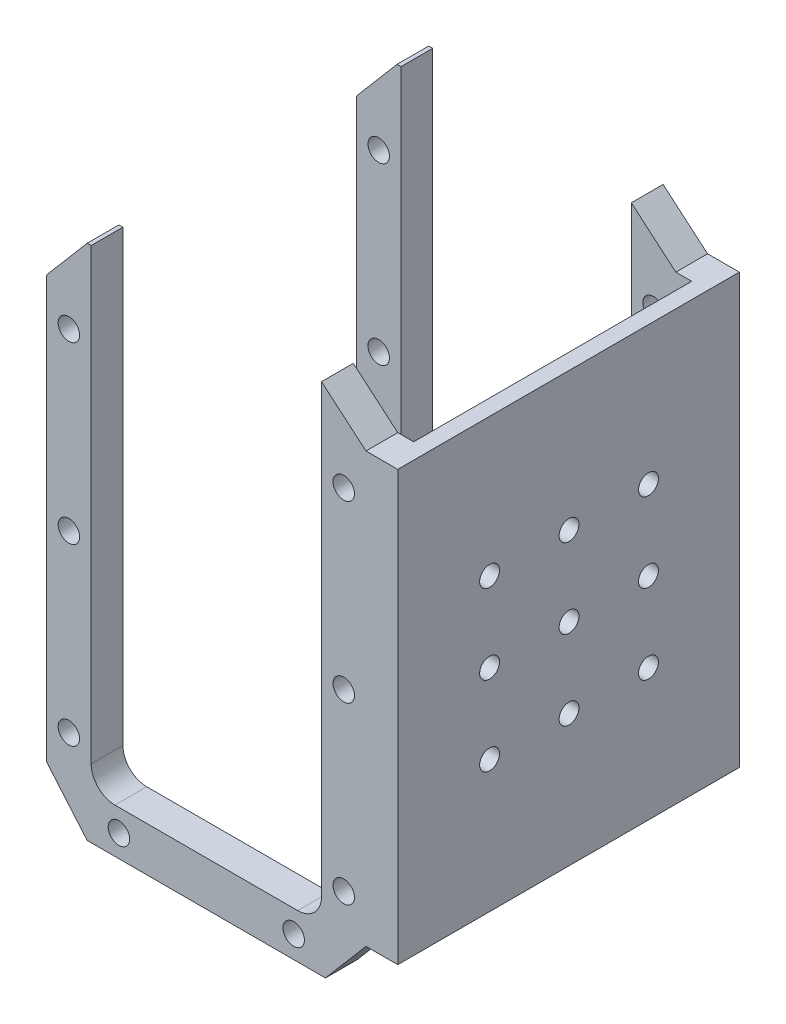
SolidWorks part; units mm, degrees
ref_plane "정면" through (0, 0, 0) normal (0, 0, 1) x (1, 0, 0)
ref_plane "윗면" through (0, 0, 0) normal (0, 1, 0) x (1, 0, 0)
ref_plane "우측면" through (0, 0, 0) normal (1, 0, 0) x (0, 0, -1)
sketch "스케치2" plane through (0, 0, 0) normal (0, 0, 1) x (1, 0, 0)
  line L0 (-19.9258, 26.8349) -> (-19.9258, -26.2651)
  line L1 (-19.9258, -26.2651) -> (-14.8258, -32.2651)
  line L2 (-14.8258, -32.2651) -> (15.1742, -32.2651)
  line L3 (15.1742, -32.2651) -> (20.2742, -26.2651)
  line L4 (20.2742, -26.2651) -> (20.2742, 27.7349)
  line L5 (20.2742, 27.7349) -> (14.6742, 32.4949)
  line L7 (14.6742, 29.8349) -> (14.6742, -23.6651)
  line L8 (11.6742, -26.6651) -> (-11.3258, -26.6651)
  line L9 (-14.3258, -23.6651) -> (-14.3258, 29.8349)
  line L10 (-14.3258, 32.8349) -> (-14.8258, 32.8349)
  line L11 (-14.8258, 32.8349) -> (-19.9258, 26.8349)
  line L12 (-14.3258, 29.8349) -> (-14.3258, 32.8349)
  line L13 (14.6742, 32.4949) -> (14.6742, 29.8349)
  circle A0 centre (17.4742, -21.6651) radius 1.35
  arc A2 (11.6742, -26.6651) -> (14.6742, -23.6651) centre (11.6742, -23.6651) ccw
  arc A3 (-14.3258, -23.6651) -> (-11.3258, -26.6651) centre (-11.3258, -23.6651) ccw
  circle A5 centre (-17.1258, 22.3349) radius 1.35
  circle A6 centre (-17.1258, 0.3349) radius 1.35
  circle A7 centre (-17.1258, -21.6651) radius 1.35
  circle A8 centre (-10.8258, -29.4651) radius 1.35
  circle A9 centre (11.1742, -29.4651) radius 1.35
  circle A10 centre (17.4742, 0.3349) radius 1.35
  circle A11 centre (17.4742, 22.3349) radius 1.35
  dimension "D1" = 2.7
  dimension "D2" = 3
  dimension "D3" = 11.1742
  dimension "D4" = 14.6742
  dimension "D5" = 15.1742
  dimension "D6" = 17.4742
  dimension "D7" = 20.2742
  dimension "D8" = 10.8258
  dimension "D9" = 14.3258
  dimension "D10" = 14.8258
  dimension "D11" = 17.1258
  dimension "D12" = 0.3349
  dimension "D13" = 22.3349
  dimension "D14" = 26.8349
  dimension "D15" = 27.7349
  dimension "D16" = 29.8349
  dimension "D17" = 32.4949
  dimension "D18" = 26.2651
  dimension "D19" = 21.6651
  dimension "D21" = 26.6651
  dimension "D22" = 29.4651
extrude "보스-돌출2" add sketch "스케치2" along normal blind 43
sketch "스케치5" plane through (20.2742, 0, 0) normal (1, 0, 0) x (0, 0, -1)
  line L1 (-39, 32.8349) -> (-39, -26.2651)
  line L2 (-43, 32.8349) -> (0, 32.8349) construction
  line L3 (-43, -26.2651) -> (0, -26.2651) construction
  line L4 (-4, -26.2651) -> (-4, -32.2651)
  line L5 (-4, -26.2651) -> (-4, 32.8349)
  line L6 (-4, 32.8349) -> (-39, 32.8349)
  line L7 (-43, -26.2651) -> (-43, 27.7349) construction
  line L8 (0, -26.2651) -> (0, 27.7349) construction
  line L9 (-43, -32.2651) -> (0, -32.2651) construction
  line L10 (-4, -32.2651) -> (-39, -32.2651)
  line L11 (-39, -32.2651) -> (-39, -26.2651)
  dimension "D1" = 4
  dimension "D2" = 4
extrude "컷-돌출3" cut sketch "스케치5" against normal blind 43
sketch "스케치6" plane through (0, 0, 43) normal (0, 0, 1) x (1, 0, 0)
  line L0 (20.2742, 27.7349) -> (24.2742, 27.7349)
  line L1 (24.2742, 27.7349) -> (24.2742, -26.2651)
  line L2 (20.2742, 27.7349) -> (20.2742, -26.2651)
  line L3 (20.2742, -26.2651) -> (24.2742, -26.2651)
  dimension "D1" = 4
extrude "보스-돌출3" add sketch "스케치6" against normal blind 43
sketch "스케치7" plane through (0, 27.7349, 0) normal (0, 1, 0) x (1, 0, 0)
  line L0 (20.2742, -4) -> (22.2742, -4)
  line L1 (22.2742, -4) -> (22.2742, -39)
  line L4 (20.2742, -39) -> (20.2742, -4)
  line L5 (24.2742, 0) -> (24.2742, -43) construction
  line L6 (20.2742, -39) -> (22.2742, -39)
  dimension "D1" = 2
extrude "컷-돌출5" cut sketch "스케치7" against normal blind 54
sketch "스케치8" plane through (24.2742, 0, 0) normal (1, 0, 0) x (0, 0, -1)
  line L0 (-21.5, 27.7349) -> (-21.5, -26.2651) construction
  line L1 (0, 27.7349) -> (-43, 27.7349) construction
  line L2 (0, -26.2651) -> (-43, -26.2651) construction
  line L3 (0, 0) -> (-43, 0.7349) construction
  line L4 (-43, -26.2651) -> (-43, 27.7349) construction
  line L5 (-21.4727, 23.4085) -> (-21.4727, 5.6268) construction
  line L6 (1.0273, 0.3585) -> (-12.6919, 0.3585) construction
  line L7 (-21.4727, 1.5902) -> (-21.4727, -0.9091) construction
  line L8 (-26.7411, 0.3585) -> (-43.9727, 0.3585) construction
  line L9 (-21.4727, -4.9099) -> (-21.4727, -22.6915) construction
  line L10 (-20.1922, 0.3585) -> (-22.6919, 0.3585) construction
  circle A0 centre (-21.4421, 0.3406) radius 1.25
  circle A1 centre (-31.4421, 10.3406) radius 1.25
  circle A2 centre (-11.4421, 0.3406) radius 1.25
  circle A3 centre (-21.4421, 10.3406) radius 1.25
  circle A4 centre (-31.4421, 0.3406) radius 1.25
  circle A5 centre (-11.4421, 10.3406) radius 1.25
  circle A6 centre (-31.4421, -9.6594) radius 1.25
  circle A7 centre (-21.4421, -9.6594) radius 1.25
  circle A8 centre (-11.4421, -9.6594) radius 1.25
  dimension "D1" = 2.5
  dimension "D2" = 11.5579
  dimension "D3" = 21.5273
  dimension "D4" = 21.5579
  dimension "D5" = 31.5579
  dimension "D6" = 16.6056
  dimension "D7" = 26.6056
  dimension "D8" = 26.6235
  dimension "D9" = 36.6056
extrude "컷-돌출6" cut sketch "스케치8" against normal blind 54
